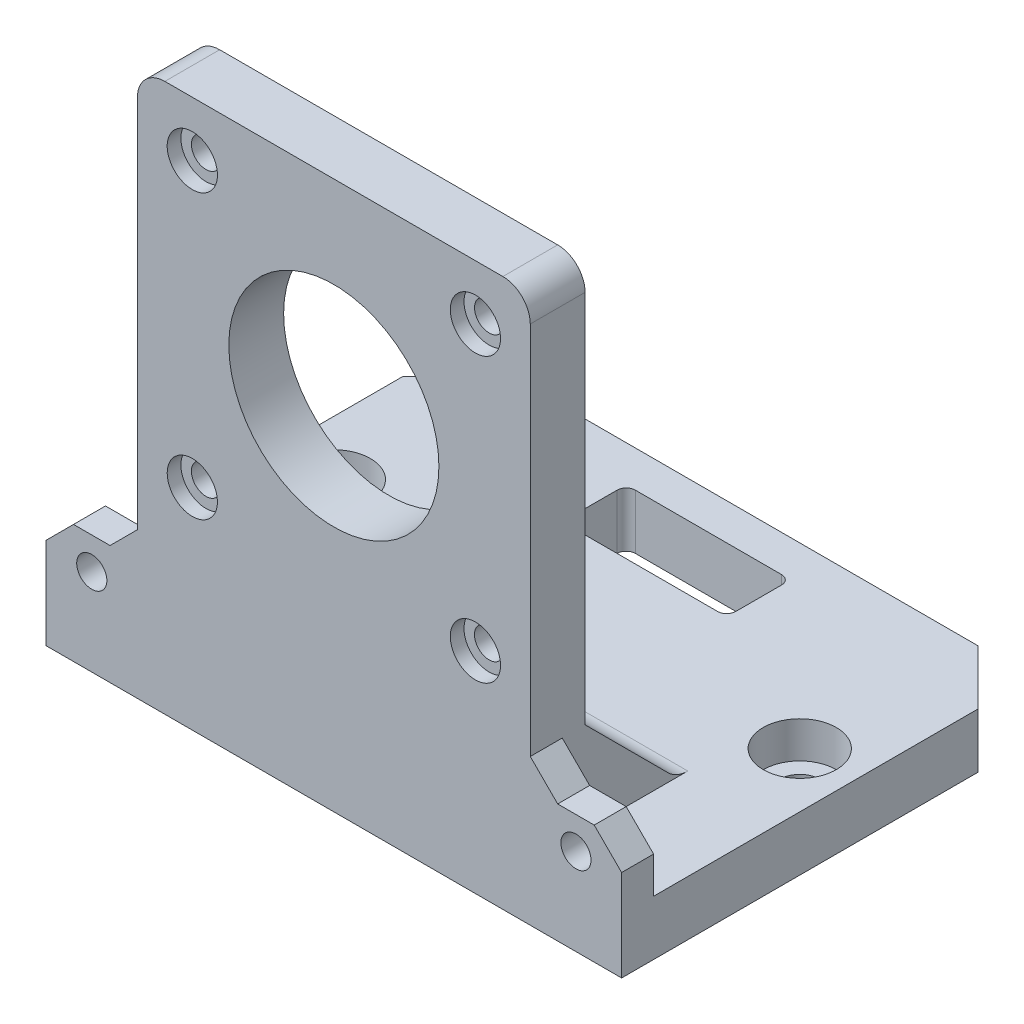
SolidWorks part; units mm, degrees
ref_plane "Front Plane" through (0, 0, 0) normal (0, 0, 1) x (1, 0, 0)
ref_plane "Top Plane" through (0, 0, 0) normal (0, 1, 0) x (1, 0, 0)
ref_plane "Right Plane" through (0, 0, 0) normal (1, 0, 0) x (0, 0, -1)
sketch "Sketch1" plane through (0, 0, 0) normal (0, 0, 1) x (1, 0, 0)
  line L0 (0, 15.495) -> (0, 0) construction
  line L1 (-15.495, -15.495) -> (15.495, -15.495) construction
  line L2 (-15.495, -15.495) -> (-15.495, 15.495) construction
  line L3 (-15.495, 15.495) -> (15.495, 15.495) construction
  line L4 (15.495, -15.495) -> (15.495, 15.495) construction
  line L5 (-15.495, -15.495) -> (15.495, 15.495) construction
  line L6 (-15.495, 15.495) -> (15.495, -15.495) construction
  line L7 (0, 0) -> (-15.495, 0) construction
  line L9 (-21.5, -32.5) -> (21.5, -32.5)
  line L10 (-21.5, -32.5) -> (-21.5, 21.5)
  line L11 (-21.5, 21.5) -> (21.5, 21.5)
  line L12 (21.5, -32.5) -> (21.5, 21.5)
  circle A0 centre (-15.495, 15.495) radius 1.6
  circle A1 centre (15.495, 15.495) radius 1.6
  circle A2 centre (15.495, -15.495) radius 1.6
  circle A3 centre (-15.495, -15.495) radius 1.6
  circle A4 centre (0, 0) radius 11.5
  point P0 (0, 0)
  dimension "D3" = 3.2
  dimension "D4" = 23
  dimension "D1" = 30.99
  dimension "D2" = 30.99
  dimension "D5" = 43
  dimension "D6" = 54
extrude "Boss-Extrude1" add sketch "Sketch1" along normal blind 6
fillet "Fillet1" radius 3 2 edges at (21.5, 21.5, 3) (-21.5, 21.5, 3)
sketch "Sketch2" plane through (0, -32.5, 0) normal (0, -1, 0) x (1, 0, 0)
  line L1 (-31.5, 6) -> (31.5, 6)
  line L2 (-31.5, 6) -> (-31.5, -39)
  line L3 (-31.5, -39) -> (31.5, -39)
  line L4 (31.5, 6) -> (31.5, -39)
  line L5 (-21.5, 6) -> (-21.5, 0) construction
  line L6 (21.5, 6) -> (21.5, 0) construction
  line L7 (-21.5, 6) -> (21.5, 6) construction
  dimension "D1" = 45
  dimension "D2" = 10
  dimension "D3" = 10
extrude "Boss-Extrude2" add sketch "Sketch2" along normal blind 6
sketch "Sketch3" plane through (0, -32.5, 0) normal (0, 1, 0) x (1, 0, 0)
  line L0 (-25.5, 39) -> (-25.5, 0) construction
  line L1 (-31.5, 39) -> (31.5, 39) construction
  line L2 (-21.5, 0) -> (21.5, 0) construction
  line L3 (-31.5, -6) -> (-31.5, 39) construction
  line L4 (0, 39) -> (0, 0) construction
  circle A0 centre (-25.5, 19.5) radius 2.2
  circle A1 centre (25.5, 19.5) radius 2.2
  dimension "D2" = 4.4
  dimension "D1" = 6
extrude "Cut-Extrude1" cut sketch "Sketch3" against normal blind 10
chamfer "Chamfer6" distance 10 angle 45 1 edges at (0, -32.5, 0)
sketch "Sketch7" plane through (0, 0, 6) normal (0, 0, 1) x (1, 0, 0)
  line L0 (0, 21.5) -> (0, 0) construction
  line L1 (18.5, 21.5) -> (-18.5, 21.5) construction
  line L2 (0, 0) -> (-6.9142, 0) construction
  circle A0 centre (-15.495, 15.495) radius 2.75
  circle A1 centre (15.495, 15.495) radius 2.75
  circle A2 centre (15.495, -15.495) radius 2.75
  circle A3 centre (-15.495, -15.495) radius 2.75
  dimension "D1" = 5.5
extrude "Cut-Extrude4" cut sketch "Sketch7" against normal blind 1.5
ref_plane "Plane1" through (0, 0, 0) normal (1, 0, 0) x (0, 0, -1)
ref_plane "Plane2" through (-21.15, 0, 0) normal (-1, 0, 0) x (0, 0, 1)
chamfer "Chamfer11" distance 6 angle 45 2 edges at (31.5, -35.5, -39) (-31.5, -35.5, -39)
sketch "Sketch13" plane through (0, -32.5, 0) normal (0, 1, 0) x (1, 0, 0)
  line L0 (-21.5, -6) -> (-31.5, -6) construction
  line L1 (-31.5, -6) -> (-21.5, -6)
  line L2 (-31.5, -6) -> (-31.5, -2.5)
  line L3 (-31.5, -2.5) -> (-21.5, -2.5)
  line L4 (-21.5, -6) -> (-21.5, -2.5)
  line L5 (-31.5, -6) -> (-31.5, 33) construction
  line L6 (-21.5, -6) -> (-21.5, 10) construction
  line L7 (0, 0) -> (0, 18.5124) construction
  line L8 (21.5, -6) -> (21.5, -2.5)
  line L9 (31.5, -2.5) -> (21.5, -2.5)
  line L10 (31.5, -6) -> (31.5, -2.5)
  line L11 (31.5, -6) -> (21.5, -6)
  dimension "D1" = 3.5
extrude "Boss-Extrude7" add sketch "Sketch13" along normal blind 7
sketch "Sketch14" plane through (0, 0, 6) normal (0, 0, 1) x (1, 0, 0)
  line L0 (-26.5, -25.5) -> (-26.5, -32.5) construction
  line L1 (-31.5, -25.5) -> (-21.5, -25.5) construction
  line L2 (31.5, -38.5) -> (-31.5, -38.5) construction
  line L3 (0, 21.5) -> (0, -29) construction
  line L4 (18.5, 21.5) -> (-18.5, 21.5) construction
  circle A0 centre (-26.5, -29) radius 1.65
  circle A1 centre (26.5, -29) radius 1.65
  dimension "D2" = 3.3
  dimension "D1" = 6
extrude "Cut-Extrude5" cut sketch "Sketch14" against normal blind 7
sketch "Sketch15" plane through (0, -32.5, 0) normal (0, 1, 0) x (1, 0, 0)
  line L0 (0, 39) -> (0, 0) construction
  line L1 (-25.5, 39) -> (25.5, 39) construction
  line L3 (-9, 28) -> (9, 28)
  line L4 (-9, 28) -> (-9, 35)
  line L5 (-9, 35) -> (9, 35)
  line L6 (9, 28) -> (9, 35)
  line L7 (-9, 28) -> (9, 35) construction
  line L8 (-9, 35) -> (9, 28) construction
  point P5 (0, 31.5)
  dimension "D1" = 7
  dimension "D2" = 18
  dimension "D3" = 4
extrude "Cut-Extrude6" cut sketch "Sketch15" against normal blind 7
fillet "Fillet9" radius 1 4 edges at (9, -35.5, -28) (-9, -35.5, -28) (-9, -35.5, -35) (9, -35.5, -35)
fillet "Fillet10" radius 3 1 edges at (0, -32.5, -10)
sketch "Sketch16" plane through (0, -32.5, 0) normal (0, 1, 0) x (1, 0, 0)
  circle A0 centre (-25.5, 19.5) radius 4
  circle A1 centre (25.5, 19.5) radius 4
  dimension "D1" = 8
  dimension "D2" = 8
extrude "Cut-Extrude7" cut sketch "Sketch16" against normal blind 4
chamfer "Chamfer12" distance 3 angle 45 4 edges at (-21.5, -25.5, 4.25) (-31.5, -25.5, 4.25) (21.5, -25.5, 4.25) (31.5, -25.5, 4.25)
